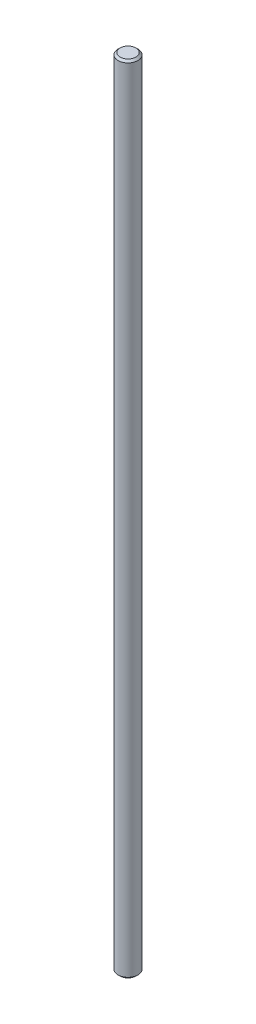
SolidWorks part; units mm, degrees
ref_plane "Front Plane" through (0, 0, 0) normal (0, 0, 1) x (1, 0, 0)
ref_plane "Top Plane" through (0, 0, 0) normal (0, 1, 0) x (1, 0, 0)
ref_plane "Right Plane" through (0, 0, 0) normal (1, 0, 0) x (0, 0, -1)
sketch "Sketch1" plane through (0, 0, 0) normal (0, 1, 0) x (1, 0, 0)
  circle A0 centre (0, 0) radius 4
  dimension "D1" = 8
extrude "Boss-Extrude1" add sketch "Sketch1" along normal blind 320
chamfer "Chamfer1" distance 0.8 angle 45 2 edges at (0, 0, 4) (0, 320, 4)
equation "\"D\"= 8"
equation "\"L\"= 320"
equation "\"D1@Sketch1\"=\"D\""
equation "\"D1@Boss-Extrude1\"=\"L\""
equation "\"D1@Chamfer1\"=\"D\"/10"
